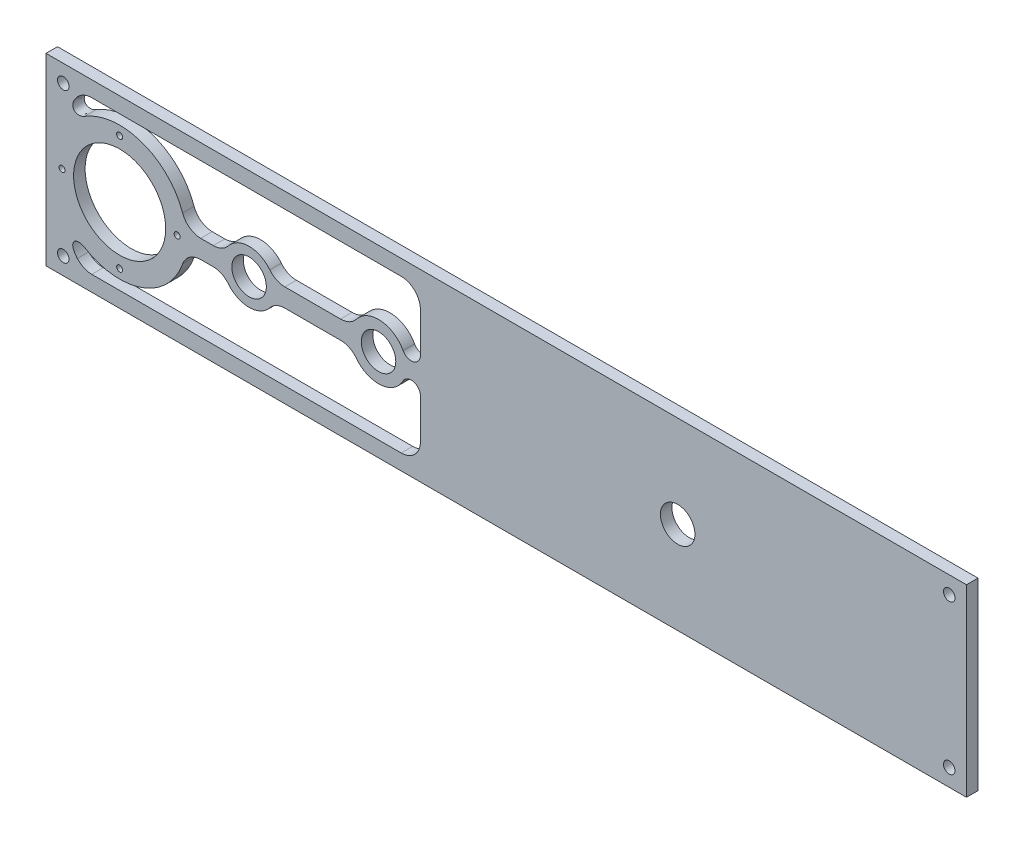
SolidWorks part; units mm, degrees
material "1060 Alloy"
ref_plane "Front Plane" through (0, 0, 0) normal (0, 0, 1) x (1, 0, 0)
ref_plane "Top Plane" through (0, 0, 0) normal (0, 1, 0) x (1, 0, 0)
ref_plane "Right Plane" through (0, 0, 0) normal (1, 0, 0) x (0, 0, -1)
sketch "Sketch1" plane through (0, 0, 0) normal (0, 0, 1) x (1, 0, 0)
  line L1 (0, 50.8) -> (508, 50.8)
  line L2 (0, 50.8) -> (0, -50.8)
  line L3 (0, -50.8) -> (508, -50.8)
  line L4 (508, 50.8) -> (508, -50.8)
  dimension "D1" = 508
  dimension "D2" = 101.6
extrude "Boss-Extrude1" add sketch "Sketch1" against normal blind 6.35
sketch "Sketch2" plane through (0, 0, 0) normal (0, 0, 1) x (1, 0, 0)
  line L0 (0, 50.8) -> (0, -50.8) construction
  circle A0 centre (40.64, 0) radius 25.4
  circle A1 centre (72.39, 0) radius 1.651
  circle A2 centre (40.64, -31.75) radius 1.651
  circle A3 centre (8.89, 0) radius 1.651
  circle A4 centre (40.64, 31.75) radius 1.651
  point P15 (40.64, 0)
  dimension "D1" = 50.8
  dimension "D2" = 3.302
  dimension "D3" = 31.75
  dimension "D4" = 40.64
  dimension "D5" = 4
extrude "Motor mount" cut sketch "Sketch2" against normal blind 6.35
sketch "Sketch3" plane through (0, 0, 0) normal (0, 0, 1) x (1, 0, 0)
  circle A0 centre (40.64, 0) radius 25.4 construction
  circle A1 centre (40.64, 0) radius 25.4 construction
  circle A2 centre (112.0775, 0) radius 9.525
  circle A3 centre (183.515, 0) radius 9.525
  circle A4 centre (348.615, 0) radius 9.525
  dimension "D1" = 19.05
  dimension "D2" = 19.05
  dimension "D5" = 19.05
  dimension "D3" = 71.4375
  dimension "D4" = 71.4375
  dimension "D6" = 165.1
extrude "Cut-Extrude2" cut sketch "Sketch3" against normal through all
sketch "Sketch4" plane through (0, 0, 0) normal (0, 0, 1) x (1, 0, 0)
  line L0 (508, 50.8) -> (0, 50.8) construction
  line L1 (0, 50.8) -> (0, -50.8) construction
  line L2 (508, -50.8) -> (508, 50.8) construction
  line L3 (0, -50.8) -> (508, -50.8) construction
  circle A0 centre (9.525, 41.275) radius 3.175
  circle A1 centre (9.525, -41.275) radius 3.175
  circle A2 centre (498.475, 41.275) radius 3.175
  circle A3 centre (498.475, -41.275) radius 3.175
  dimension "D1" = 6.35
  dimension "D2" = 6.35
  dimension "D3" = 6.35
  dimension "D4" = 6.35
  dimension "D5" = 9.525
  dimension "D6" = 9.525
  dimension "D7" = 9.525
  dimension "D8" = 9.525
extrude "Cut-Extrude3" cut sketch "Sketch4" against normal through all
sketch "Sketch7" plane through (0, 0, 0) normal (0, 0, 1) x (1, 0, 0)
  line L3 (211.7063, 0) -> (211.7063, 47.2876) construction
  line L5 (211.7063, 47.2876) -> (0, 47.2876) construction
  line L6 (0, 47.2876) -> (0, 0) construction
  line L7 (0, 0) -> (40.64, 0) construction
  line L8 (40.64, -5.08) -> (112.0775, -5.08)
  line L9 (112.0775, -5.08) -> (183.515, -5.08)
  line L10 (183.515, -5.08) -> (216.7863, -5.08)
  line L11 (216.7863, -5.08) -> (216.7863, 52.3676)
  line L12 (216.7863, 52.3676) -> (-5.08, 52.3676)
  line L13 (-5.08, 52.3676) -> (-5.08, -5.08)
  line L14 (-5.08, -5.08) -> (40.64, -5.08)
  line L15 (85.4063, 5.08) -> (92.3414, 5.08)
  line L16 (131.8136, 5.08) -> (162.5851, 5.08)
  line L18 (206.6263, 9.6628) -> (206.6263, 31.6032)
  line L19 (196.0219, 42.2076) -> (25.2631, 42.2076)
  line L20 (0, 50.8) -> (0, -50.8) construction
  line L22 (206.6263, 5.08) -> (206.6263, 42.2076) construction
  line L23 (112.0775, 5.08) -> (183.515, 5.08) construction
  line L24 (40.64, 5.08) -> (112.0775, 5.08) construction
  line L25 (206.6263, 42.2076) -> (5.08, 42.2076) construction
  line L26 (5.08, 42.2076) -> (5.08, 5.08) construction
  line L27 (112.0775, 0) -> (183.515, 0) construction
  line L28 (40.64, 0) -> (112.0775, 0) construction
  line L29 (183.515, 0) -> (211.7063, 0) construction
  line L30 (5.08, 5.08) -> (40.64, 5.08) construction
  line L31 (183.515, 5.08) -> (206.6263, 5.08) construction
  circle A0 centre (40.64, 0) radius 31.75 construction
  circle A1 centre (112.0775, 0) radius 9.525
  circle A2 centre (183.515, 0) radius 9.525
  circle A3 centre (9.525, 41.275) radius 3.1307
  arc A4 (100.6434, 9.0867) -> (92.3414, 5.08) centre (92.3414, 15.6844) cw
  arc A5 (197.0687, 7.2633) -> (206.6263, 9.6628) centre (201.5463, 9.6628) ccw
  arc A6 (17.2833, 38.5871) -> (25.2631, 42.2076) centre (25.2631, 31.6032) cw
  arc A7 (206.6263, 31.6032) -> (196.0219, 42.2076) centre (196.0219, 31.6032) ccw
  circle A8 centre (112.0775, 0) radius 4.445
  circle A9 centre (183.515, 0) radius 4.445
  circle A10 centre (40.64, 0) radius 26.67
  arc A11 (197.0687, 7.2633) -> (171.333, 9.3838) centre (183.515, 0) ccw
  arc A12 (162.5851, 5.08) -> (171.333, 9.3838) centre (162.5851, 16.1223) ccw
  arc A13 (123.5116, 9.0867) -> (100.6434, 9.0867) centre (112.0775, 0) ccw
  arc A14 (131.8136, 5.08) -> (123.5116, 9.0867) centre (131.8136, 15.6844) cw
  arc A15 (75.3984, 12.178) -> (21.2634, 31.3209) centre (40.64, 0) ccw
  arc A17 (75.3984, 12.178) -> (85.4063, 5.08) centre (85.4063, 15.6844) ccw
  spline S0 degree 3 poles (17.2833, 38.5871) (11.5305, 32.014) (16.7871, 28.5516) (21.2634, 31.3209) knots 0 0 0 0 1 1 1 1
  dimension "D1" = 5.08
  dimension "D3" = 5.08
  dimension "D4" = 11.0423
  dimension "D5" = 10.6044
  dimension "D6" = 10.6044
  dimension "D7" = 10.6044
  dimension "D2" = 5.08
extrude "Cut-Extrude4" cut sketch "Sketch7" against normal through all contours L19 A6 S0 A15 A17 L15 A4 A13 A14 L16 A12 A11 A5 L18 A7
mirror "Mirror1" about plane through (0, 0, 0) normal (0, 1, 0) of "Cut-Extrude4"
